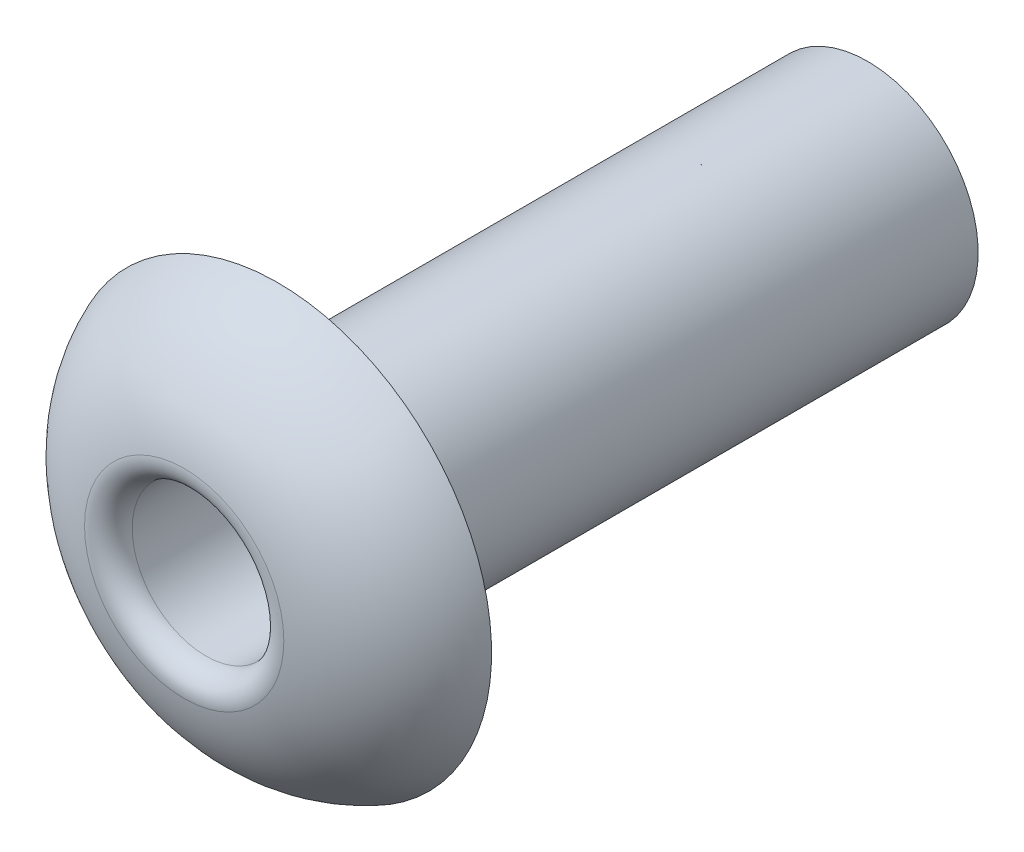
SolidWorks part; units mm, degrees
material "AISI 304"
ref_plane "前视基准面" through (0, 0, 0) normal (0, 0, 1) x (1, 0, 0)
ref_plane "上视基准面" through (0, 0, 0) normal (0, 1, 0) x (1, 0, 0)
ref_plane "右视基准面" through (0, 0, 0) normal (1, 0, 0) x (0, 0, -1)
sketch "草图1" plane through (0, 0, 0) normal (1, 0, 0) x (0, 0, -1)
  line L0 (0, 1.5) -> (0, 2.9)
  line L1 (0, 1.5) -> (8, 1.5)
  line L2 (8, 1.5) -> (8, 1)
  line L3 (4, 0) -> (0, 0) construction
  line L4 (-1.3, 0) -> (-1.3, -1.4133) construction
  line L5 (8, 1) -> (-1.3, 1)
  line L6 (-1.3, 0) -> (-1.3, 1) construction
  arc A0 (0, 2.9) -> (-1.3, 1) centre (0.7385, 1) ccw
  dimension "D1" = 5.8
  dimension "D2" = 1.3
  dimension "D3" = 8
  dimension "D4" = 2
  dimension "D5" = 3
revolve "旋转1" add sketch "草图1" angle 360 about L3
fillet "装饰圆角" radius 0.3 1 edges at (-1, 0, 1.3)
